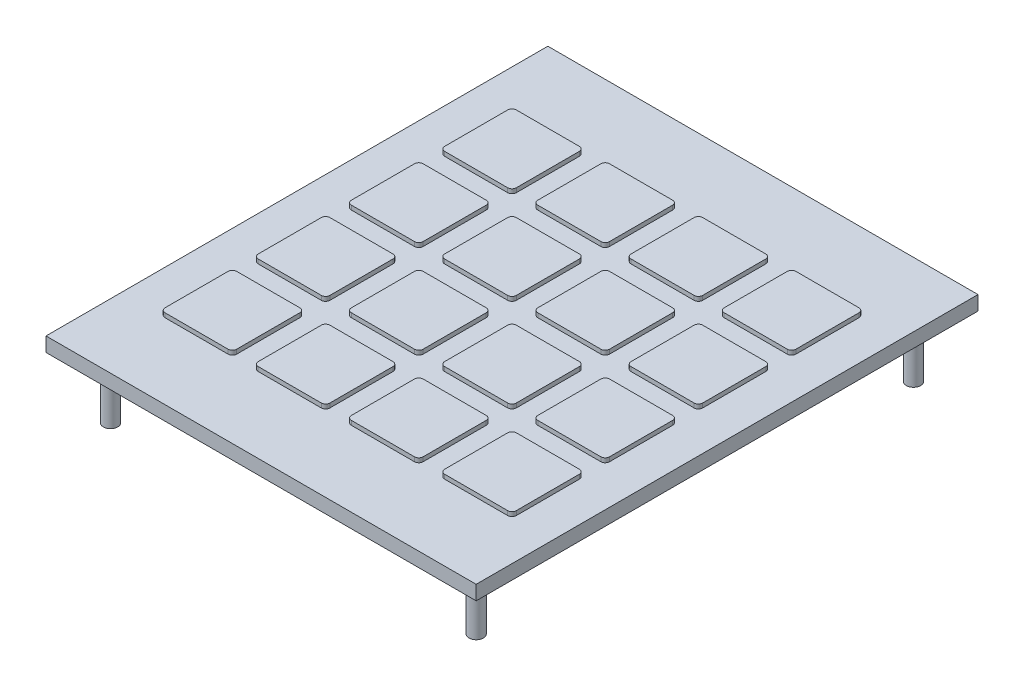
SolidWorks part; units mm, degrees
ref_plane "Front Plane" through (0, 0, 0) normal (0, 0, 1) x (1, 0, 0)
ref_plane "Top Plane" through (0, 0, 0) normal (0, 1, 0) x (1, 0, 0)
ref_plane "Right Plane" through (0, 0, 0) normal (1, 0, 0) x (0, 0, -1)
sketch "Sketch1" plane through (0, 0, 0) normal (0, 1, 0) x (1, 0, 0)
  line L1 (-29.878, 14.8171) -> (30.122, 14.8171)
  line L2 (-29.878, 14.8171) -> (-29.878, -55.1829)
  line L3 (-29.878, -55.1829) -> (30.122, -55.1829)
  line L4 (30.122, 14.8171) -> (30.122, -55.1829)
  dimension "D1" = 60
  dimension "D2" = 70
extrude "Boss-Extrude1" add sketch "Sketch1" along normal blind 2
sketch "Sketch2" plane through (0, 2, 0) normal (0, 1, 0) x (1, 0, 0)
  line L0 (-29.878, 14.8171) -> (-29.878, -55.1829) construction
  line L1 (-23.778, 4.3171) -> (-14.978, 4.3171)
  line L2 (-24.378, 3.7171) -> (-24.378, -5.0829)
  line L3 (-23.778, -5.6829) -> (-14.978, -5.6829)
  line L4 (-14.378, 3.7171) -> (-14.378, -5.0829)
  line L5 (30.122, 14.8171) -> (-29.878, 14.8171) construction
  line L6 (-10.778, 4.3171) -> (-1.978, 4.3171)
  line L7 (-11.378, 3.7171) -> (-11.378, -5.0829)
  line L8 (-10.778, -5.6829) -> (-1.978, -5.6829)
  line L9 (-1.378, 3.7171) -> (-1.378, -5.0829)
  line L10 (2.222, 4.3171) -> (11.022, 4.3171)
  line L11 (1.622, 3.7171) -> (1.622, -5.0829)
  line L12 (2.222, -5.6829) -> (11.022, -5.6829)
  line L13 (11.622, 3.7171) -> (11.622, -5.0829)
  line L14 (15.222, 4.3171) -> (24.022, 4.3171)
  line L15 (14.622, 3.7171) -> (14.622, -5.0829)
  line L16 (15.222, -5.6829) -> (24.022, -5.6829)
  line L17 (24.622, 3.7171) -> (24.622, -5.0829)
  line L18 (-10.778, -8.6829) -> (-1.978, -8.6829)
  line L19 (-11.378, -9.2829) -> (-11.378, -18.0829)
  line L20 (-10.778, -18.6829) -> (-1.978, -18.6829)
  line L21 (-1.378, -9.2829) -> (-1.378, -18.0829)
  line L22 (2.222, -8.6829) -> (11.022, -8.6829)
  line L23 (1.622, -9.2829) -> (1.622, -18.0829)
  line L24 (2.222, -18.6829) -> (11.022, -18.6829)
  line L25 (11.622, -9.2829) -> (11.622, -18.0829)
  line L26 (15.222, -8.6829) -> (24.022, -8.6829)
  line L27 (14.622, -9.2829) -> (14.622, -18.0829)
  line L28 (15.222, -18.6829) -> (24.022, -18.6829)
  line L29 (24.622, -9.2829) -> (24.622, -18.0829)
  line L30 (-10.778, -21.6829) -> (-1.978, -21.6829)
  line L31 (-11.378, -22.2829) -> (-11.378, -31.0829)
  line L32 (-10.778, -31.6829) -> (-1.978, -31.6829)
  line L33 (-1.378, -22.2829) -> (-1.378, -31.0829)
  line L34 (2.222, -21.6829) -> (11.022, -21.6829)
  line L35 (1.622, -22.2829) -> (1.622, -31.0829)
  line L36 (2.222, -31.6829) -> (11.022, -31.6829)
  line L37 (11.622, -22.2829) -> (11.622, -31.0829)
  line L38 (15.222, -21.6829) -> (24.022, -21.6829)
  line L39 (14.622, -22.2829) -> (14.622, -31.0829)
  line L40 (15.222, -31.6829) -> (24.022, -31.6829)
  line L41 (24.622, -22.2829) -> (24.622, -31.0829)
  line L42 (-10.778, -34.6829) -> (-1.978, -34.6829)
  line L43 (-11.378, -35.2829) -> (-11.378, -44.0829)
  line L44 (-10.778, -44.6829) -> (-1.978, -44.6829)
  line L45 (-1.378, -35.2829) -> (-1.378, -44.0829)
  line L46 (2.222, -34.6829) -> (11.022, -34.6829)
  line L47 (1.622, -35.2829) -> (1.622, -44.0829)
  line L48 (2.222, -44.6829) -> (11.022, -44.6829)
  line L49 (11.622, -35.2829) -> (11.622, -44.0829)
  line L50 (15.222, -34.6829) -> (24.022, -34.6829)
  line L51 (14.622, -35.2829) -> (14.622, -44.0829)
  line L52 (15.222, -44.6829) -> (24.022, -44.6829)
  line L53 (24.622, -35.2829) -> (24.622, -44.0829)
  line L54 (-23.778, -8.6829) -> (-14.978, -8.6829)
  line L55 (-24.378, -9.2829) -> (-24.378, -18.0829)
  line L56 (-23.778, -18.6829) -> (-14.978, -18.6829)
  line L57 (-14.378, -9.2829) -> (-14.378, -18.0829)
  line L58 (-23.778, -21.6829) -> (-14.978, -21.6829)
  line L59 (-24.378, -22.2829) -> (-24.378, -31.0829)
  line L60 (-23.778, -31.6829) -> (-14.978, -31.6829)
  line L61 (-14.378, -22.2829) -> (-14.378, -31.0829)
  line L62 (-23.778, -34.6829) -> (-14.978, -34.6829)
  line L63 (-24.378, -35.2829) -> (-24.378, -44.0829)
  line L64 (-23.778, -44.6829) -> (-14.978, -44.6829)
  line L65 (-14.378, -35.2829) -> (-14.378, -44.0829)
  arc A0 (-24.378, -5.0829) -> (-23.778, -5.6829) centre (-23.778, -5.0829) ccw
  arc A1 (-14.978, -5.6829) -> (-14.378, -5.0829) centre (-14.978, -5.0829) ccw
  arc A2 (-14.978, 4.3171) -> (-14.378, 3.7171) centre (-14.978, 3.7171) cw
  arc A3 (-23.778, 4.3171) -> (-24.378, 3.7171) centre (-23.778, 3.7171) ccw
  arc A4 (-11.378, -5.0829) -> (-10.778, -5.6829) centre (-10.778, -5.0829) ccw
  arc A5 (-1.978, -5.6829) -> (-1.378, -5.0829) centre (-1.978, -5.0829) ccw
  arc A6 (-1.978, 4.3171) -> (-1.378, 3.7171) centre (-1.978, 3.7171) cw
  arc A7 (-10.778, 4.3171) -> (-11.378, 3.7171) centre (-10.778, 3.7171) ccw
  arc A8 (1.622, -5.0829) -> (2.222, -5.6829) centre (2.222, -5.0829) ccw
  arc A9 (11.022, -5.6829) -> (11.622, -5.0829) centre (11.022, -5.0829) ccw
  arc A10 (11.022, 4.3171) -> (11.622, 3.7171) centre (11.022, 3.7171) cw
  arc A11 (2.222, 4.3171) -> (1.622, 3.7171) centre (2.222, 3.7171) ccw
  arc A12 (14.622, -5.0829) -> (15.222, -5.6829) centre (15.222, -5.0829) ccw
  arc A13 (24.022, -5.6829) -> (24.622, -5.0829) centre (24.022, -5.0829) ccw
  arc A14 (24.022, 4.3171) -> (24.622, 3.7171) centre (24.022, 3.7171) cw
  arc A15 (15.222, 4.3171) -> (14.622, 3.7171) centre (15.222, 3.7171) ccw
  arc A16 (-11.378, -18.0829) -> (-10.778, -18.6829) centre (-10.778, -18.0829) ccw
  arc A17 (-1.978, -18.6829) -> (-1.378, -18.0829) centre (-1.978, -18.0829) ccw
  arc A18 (-1.978, -8.6829) -> (-1.378, -9.2829) centre (-1.978, -9.2829) cw
  arc A19 (-10.778, -8.6829) -> (-11.378, -9.2829) centre (-10.778, -9.2829) ccw
  arc A20 (1.622, -18.0829) -> (2.222, -18.6829) centre (2.222, -18.0829) ccw
  arc A21 (11.022, -18.6829) -> (11.622, -18.0829) centre (11.022, -18.0829) ccw
  arc A22 (11.022, -8.6829) -> (11.622, -9.2829) centre (11.022, -9.2829) cw
  arc A23 (2.222, -8.6829) -> (1.622, -9.2829) centre (2.222, -9.2829) ccw
  arc A24 (14.622, -18.0829) -> (15.222, -18.6829) centre (15.222, -18.0829) ccw
  arc A25 (24.022, -18.6829) -> (24.622, -18.0829) centre (24.022, -18.0829) ccw
  arc A26 (24.022, -8.6829) -> (24.622, -9.2829) centre (24.022, -9.2829) cw
  arc A27 (15.222, -8.6829) -> (14.622, -9.2829) centre (15.222, -9.2829) ccw
  arc A28 (-11.378, -31.0829) -> (-10.778, -31.6829) centre (-10.778, -31.0829) ccw
  arc A29 (-1.978, -31.6829) -> (-1.378, -31.0829) centre (-1.978, -31.0829) ccw
  arc A30 (-1.978, -21.6829) -> (-1.378, -22.2829) centre (-1.978, -22.2829) cw
  arc A31 (-10.778, -21.6829) -> (-11.378, -22.2829) centre (-10.778, -22.2829) ccw
  arc A32 (1.622, -31.0829) -> (2.222, -31.6829) centre (2.222, -31.0829) ccw
  arc A33 (11.022, -31.6829) -> (11.622, -31.0829) centre (11.022, -31.0829) ccw
  arc A34 (11.022, -21.6829) -> (11.622, -22.2829) centre (11.022, -22.2829) cw
  arc A35 (2.222, -21.6829) -> (1.622, -22.2829) centre (2.222, -22.2829) ccw
  arc A36 (14.622, -31.0829) -> (15.222, -31.6829) centre (15.222, -31.0829) ccw
  arc A37 (24.022, -31.6829) -> (24.622, -31.0829) centre (24.022, -31.0829) ccw
  arc A38 (24.022, -21.6829) -> (24.622, -22.2829) centre (24.022, -22.2829) cw
  arc A39 (15.222, -21.6829) -> (14.622, -22.2829) centre (15.222, -22.2829) ccw
  arc A40 (-11.378, -44.0829) -> (-10.778, -44.6829) centre (-10.778, -44.0829) ccw
  arc A41 (-1.978, -44.6829) -> (-1.378, -44.0829) centre (-1.978, -44.0829) ccw
  arc A42 (-1.978, -34.6829) -> (-1.378, -35.2829) centre (-1.978, -35.2829) cw
  arc A43 (-10.778, -34.6829) -> (-11.378, -35.2829) centre (-10.778, -35.2829) ccw
  arc A44 (1.622, -44.0829) -> (2.222, -44.6829) centre (2.222, -44.0829) ccw
  arc A45 (11.022, -44.6829) -> (11.622, -44.0829) centre (11.022, -44.0829) ccw
  arc A46 (11.022, -34.6829) -> (11.622, -35.2829) centre (11.022, -35.2829) cw
  arc A47 (2.222, -34.6829) -> (1.622, -35.2829) centre (2.222, -35.2829) ccw
  arc A48 (14.622, -44.0829) -> (15.222, -44.6829) centre (15.222, -44.0829) ccw
  arc A49 (24.022, -44.6829) -> (24.622, -44.0829) centre (24.022, -44.0829) ccw
  arc A50 (24.022, -34.6829) -> (24.622, -35.2829) centre (24.022, -35.2829) cw
  arc A51 (15.222, -34.6829) -> (14.622, -35.2829) centre (15.222, -35.2829) ccw
  arc A52 (-24.378, -18.0829) -> (-23.778, -18.6829) centre (-23.778, -18.0829) ccw
  arc A53 (-14.978, -18.6829) -> (-14.378, -18.0829) centre (-14.978, -18.0829) ccw
  arc A54 (-14.978, -8.6829) -> (-14.378, -9.2829) centre (-14.978, -9.2829) cw
  arc A55 (-23.778, -8.6829) -> (-24.378, -9.2829) centre (-23.778, -9.2829) ccw
  arc A56 (-24.378, -31.0829) -> (-23.778, -31.6829) centre (-23.778, -31.0829) ccw
  arc A57 (-14.978, -31.6829) -> (-14.378, -31.0829) centre (-14.978, -31.0829) ccw
  arc A58 (-14.978, -21.6829) -> (-14.378, -22.2829) centre (-14.978, -22.2829) cw
  arc A59 (-23.778, -21.6829) -> (-24.378, -22.2829) centre (-23.778, -22.2829) ccw
  arc A60 (-24.378, -44.0829) -> (-23.778, -44.6829) centre (-23.778, -44.0829) ccw
  arc A61 (-14.978, -44.6829) -> (-14.378, -44.0829) centre (-14.978, -44.0829) ccw
  arc A62 (-14.978, -34.6829) -> (-14.378, -35.2829) centre (-14.978, -35.2829) cw
  arc A63 (-23.778, -34.6829) -> (-24.378, -35.2829) centre (-23.778, -35.2829) ccw
  point P10 (-24.378, -5.6829)
  point P15 (-14.378, 4.3171)
  point P18 (-24.378, 4.3171)
  dimension "D5" = 0.6
  dimension "D1" = 10
  dimension "D2" = 10
  dimension "D3" = 5.5
  dimension "D4" = 10.5
  dimension "D6" = 4
  dimension "D7" = 4
extrude "Boss-Extrude2" add sketch "Sketch2" along normal blind 0.6
sketch "Sketch3" plane through (0, 0, 0) normal (0, -1, 0) x (1, 0, 0)
  line L0 (-29.878, -14.8171) -> (-29.878, 55.1829) construction
  line L3 (30.122, -14.8171) -> (-29.878, -14.8171) construction
  circle A0 centre (25.622, -10.3171) radius 1
  circle A1 centre (-25.378, -10.3171) radius 1
  circle A2 centre (25.622, 50.6829) radius 1
  circle A3 centre (-25.378, 50.6829) radius 1
  dimension "D1" = 2
  dimension "D2" = 2
  dimension "D3" = 51
  dimension "D4" = 4.5
  dimension "D5" = 4.5
  dimension "D6" = 2
extrude "Boss-Extrude3" add sketch "Sketch3" along normal blind 8.5
